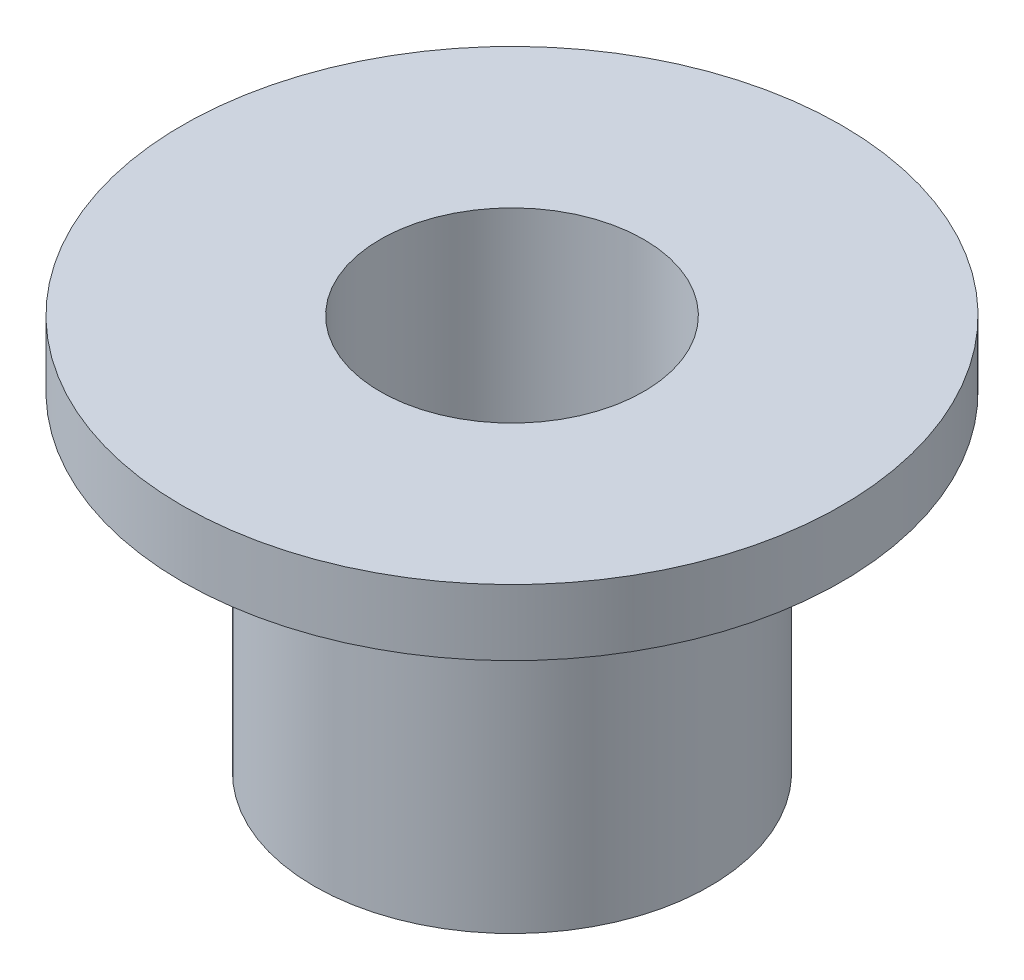
SolidWorks part; units mm, degrees
ref_plane "Front Plane" through (0, 0, 0) normal (0, 0, 1) x (1, 0, 0)
ref_plane "Top Plane" through (0, 0, 0) normal (0, 1, 0) x (1, 0, 0)
ref_plane "Right Plane" through (0, 0, 0) normal (1, 0, 0) x (0, 0, -1)
sketch "Sketch2" plane through (0, 0, 0) normal (0, 0, 1) x (1, 0, 0)
  line L0 (-2, 0) -> (-2, 6)
  line L1 (-2, 6) -> (-5, 6)
  line L2 (-5, 6) -> (-5, 5)
  line L3 (-5, 5) -> (-3, 5)
  line L4 (-3, 5) -> (-3, 0)
  line L5 (-3, 0) -> (-2, 0)
  line L6 (-2, 0) -> (0, 0) construction
  line L7 (0, 0) -> (0, 2.2598) construction
  point P2 (0, 2.2598)
  dimension "D1" = 1
  dimension "D2" = 2
  dimension "D3" = 1
  dimension "D4" = 6
  dimension "D5" = 2
  dimension "D6" = 5
revolve "Revolve1" add sketch "Sketch2" angle 360 about L7
